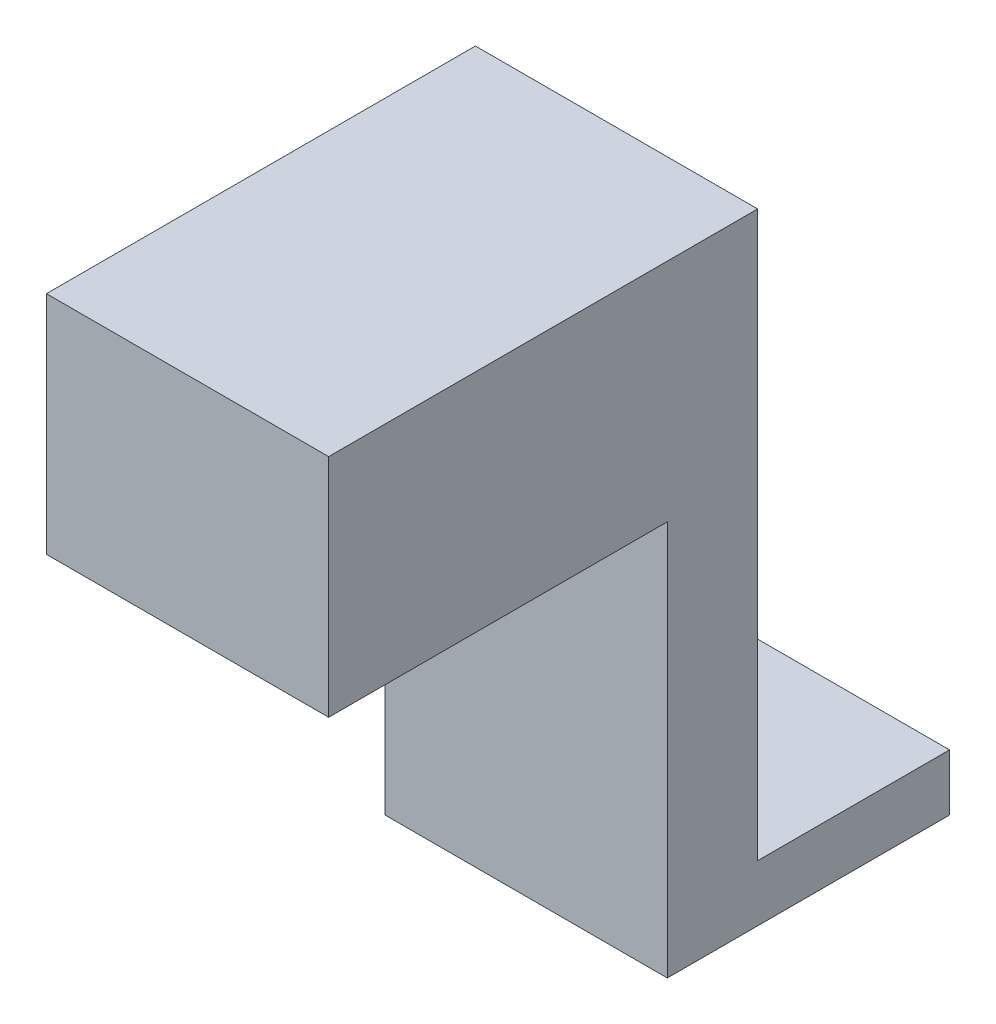
SolidWorks part; units mm, degrees
ref_plane "Front Plane" through (0, 0, 0) normal (0, 0, 1) x (1, 0, 0)
ref_plane "Top Plane" through (0, 0, 0) normal (0, 1, 0) x (1, 0, 0)
ref_plane "Right Plane" through (0, 0, 0) normal (1, 0, 0) x (0, 0, -1)
sketch "Sketch1" plane through (0, 0, 0) normal (0, 1, 0) x (1, 0, 0)
  line L1 (12.5, -12.5) -> (-12.5, -12.5)
  line L2 (12.5, -12.5) -> (12.5, 12.5)
  line L3 (12.5, 12.5) -> (-12.5, 12.5)
  line L4 (-12.5, -12.5) -> (-12.5, 12.5)
  line L5 (12.5, -12.5) -> (-12.5, 12.5) construction
  line L6 (12.5, 12.5) -> (-12.5, -12.5) construction
  point P0 (0, 0)
  dimension "D1" = 25
  dimension "D2" = 25
extrude "Boss-Extrude1" add sketch "Sketch1" along normal blind 5
sketch "Sketch2" plane through (0, 5, 0) normal (0, 1, 0) x (1, 0, 0)
  line L0 (12.5, -12.5) -> (12.5, 12.5) construction
  line L1 (-12.5, -12.5) -> (12.5, -12.5)
  line L2 (-12.5, -12.5) -> (-12.5, -4.5)
  line L3 (-12.5, -4.5) -> (12.5, -4.5)
  line L4 (12.5, -12.5) -> (12.5, -4.5)
  dimension "D1" = 8
extrude "Boss-Extrude2" add sketch "Sketch2" along normal blind 50
sketch "Sketch3" plane through (0, 0, 12.5) normal (0, 0, 1) x (1, 0, 0)
  line L0 (12.5, 55) -> (12.5, 0) construction
  line L1 (-12.5, 55) -> (12.5, 55)
  line L2 (-12.5, 55) -> (-12.5, 35)
  line L3 (-12.5, 35) -> (12.5, 35)
  line L4 (12.5, 55) -> (12.5, 35)
  dimension "D1" = 20
extrude "Boss-Extrude3" add sketch "Sketch3" along normal blind 30
